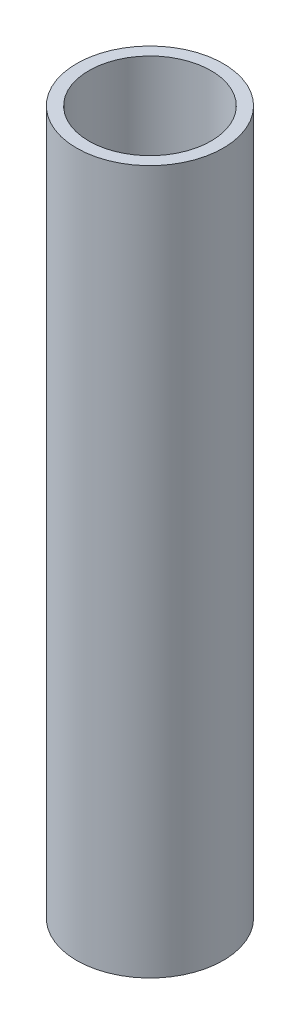
SolidWorks part; units mm, degrees
material "1060 Alloy"
ref_plane "Front Plane" through (0, 0, 0) normal (0, 0, 1) x (1, 0, 0)
ref_plane "Top Plane" through (0, 0, 0) normal (0, 1, 0) x (1, 0, 0)
ref_plane "Right Plane" through (0, 0, 0) normal (1, 0, 0) x (0, 0, -1)
sketch "Sketch1" plane through (0, 0, 0) normal (0, 1, 0) x (1, 0, 0)
  circle A0 centre (0, 0) radius 38.1
  dimension "D1" = 76.2
extrude "Boss-Extrude1" add sketch "Sketch1" along normal blind 365.76
sketch "Sketch2" plane through (0, 365.76, 0) normal (0, 1, 0) x (1, 0, 0)
  circle A0 centre (0, 0) radius 31.75
  circle A1 centre (0, 0) radius 38.1 construction
  dimension "D1" = 6.35
extrude "Cut-Extrude1" cut sketch "Sketch2" against normal through all
